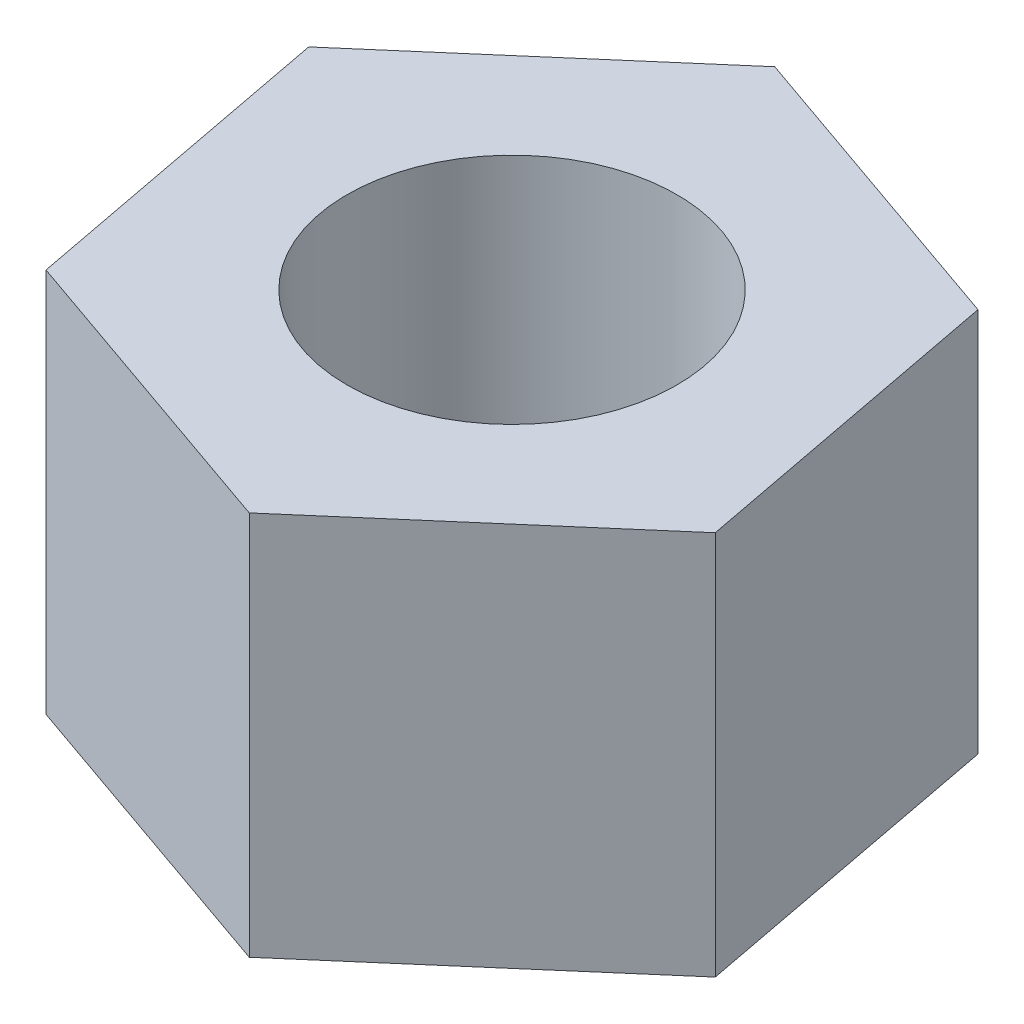
SolidWorks part; units mm, degrees
ref_plane "前视基准面" through (0, 0, 0) normal (0, 0, 1) x (1, 0, 0)
ref_plane "上视基准面" through (0, 0, 0) normal (0, 1, 0) x (1, 0, 0)
ref_plane "右视基准面" through (0, 0, 0) normal (1, 0, 0) x (0, 0, -1)
other "Configuration Table"
sketch "草图1" plane through (0, 0, 0) normal (0, 1, 0) x (1, 0, 0)
  line L1 (0.5623, -2.9519) -> (2.8376, -0.989)
  line L2 (2.8376, -0.989) -> (2.2753, 1.9629)
  line L3 (2.2753, 1.9629) -> (-0.5623, 2.9519)
  line L4 (-0.5623, 2.9519) -> (-2.8376, 0.989)
  line L5 (-2.8376, 0.989) -> (-2.2753, -1.9629)
  line L6 (-2.2753, -1.9629) -> (0.5623, -2.9519)
  circle A0 centre (0, 0) radius 2.6024 construction
  dimension "D1" = 6.01
extrude "凸台-拉伸1" add sketch "草图1" along normal blind 3.5
sketch "草图2" plane through (0, 3.5, 0) normal (0, 1, 0) x (1, 0, 0)
  circle A0 centre (0, 0) radius 1.5
  dimension "D1" = 3
extrude "切除-拉伸1" cut sketch "草图2" against normal through all
